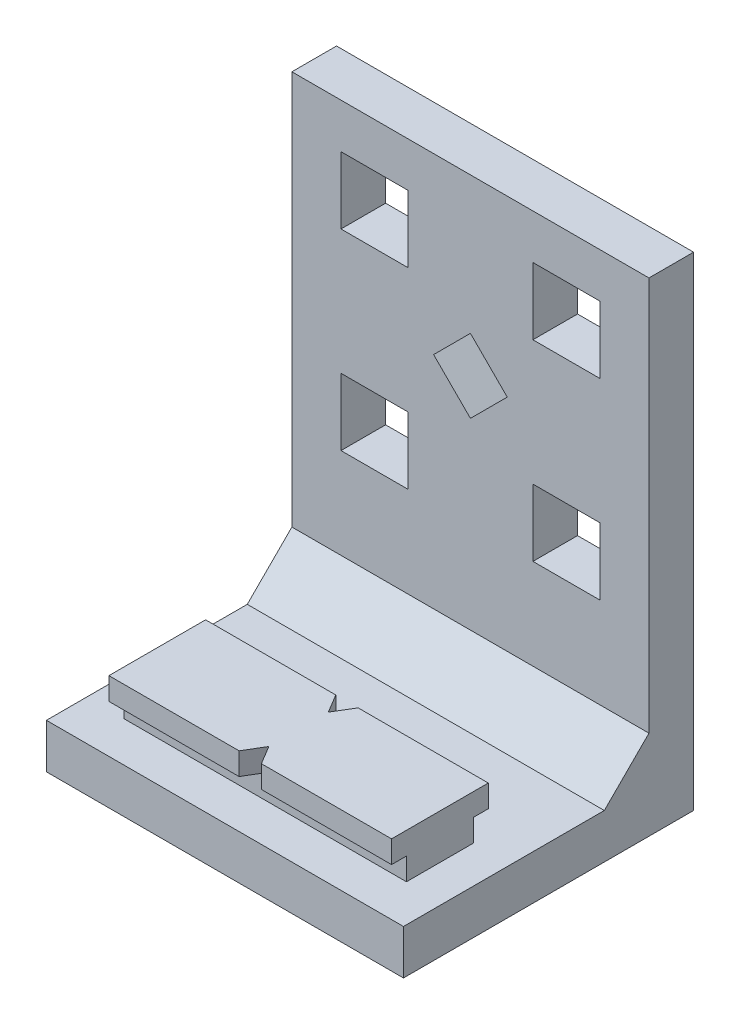
SolidWorks part; units mm, degrees
ref_plane "Front Plane" through (0, 0, 0) normal (0, 0, 1) x (1, 0, 0)
ref_plane "Top Plane" through (0, 0, 0) normal (0, 1, 0) x (1, 0, 0)
ref_plane "Right Plane" through (0, 0, 0) normal (1, 0, 0) x (0, 0, -1)
sketch "Sketch1" plane through (0, 0, 0) normal (0, 1, 0) x (1, 0, 0)
  line L1 (-12, -9.75) -> (12, -9.75)
  line L2 (-12, -9.75) -> (-12, 9.75)
  line L3 (-12, 9.75) -> (12, 9.75)
  line L4 (12, -9.75) -> (12, 9.75)
  line L5 (-12, -9.75) -> (12, 9.75) construction
  line L6 (-12, 9.75) -> (12, -9.75) construction
  point P0 (0, 0)
  dimension "D1" = 19.5
  dimension "D2" = 24
extrude "Boss-Extrude1" add sketch "Sketch1" along normal blind 3
sketch "Sketch3" plane through (0, 3, 0) normal (0, 1, 0) x (1, 0, 0)
  line L0 (-12, -9.75) -> (12, -9.75) construction
  line L1 (-9.5, -7.05) -> (9.5, -7.05)
  line L2 (-9.5, -7.05) -> (-9.5, -2.55)
  line L3 (-9.5, -2.55) -> (9.5, -2.55)
  line L4 (9.5, -7.05) -> (9.5, -2.55)
  line L5 (-9.5, -7.05) -> (9.5, -2.55) construction
  line L6 (-9.5, -2.55) -> (9.5, -7.05) construction
  point P0 (0, -4.8)
  dimension "D1" = 4.5
  dimension "D2" = 2.7
  dimension "D3" = 19
extrude "Boss-Extrude2" add sketch "Sketch3" along normal blind 1.5
sketch "Sketch4" plane through (0, 4.5, 0) normal (0, 1, 0) x (1, 0, 0)
  line L3 (9.5, -7.05) -> (9.5, -2.55) construction
  line L4 (-9.5, -8.05) -> (9.5, -8.05)
  line L5 (-9.5, -8.05) -> (-9.5, -1.55)
  line L6 (-9.5, -1.55) -> (9.5, -1.55)
  line L7 (9.5, -8.05) -> (9.5, -1.55)
  line L8 (-9.5, -8.05) -> (9.5, -1.55) construction
  line L9 (-9.5, -1.55) -> (9.5, -8.05) construction
  line L10 (-9.5, -2.55) -> (-9.5, -7.05) construction
  line L11 (9.5, -2.55) -> (-9.5, -2.55) construction
  line L12 (-9.5, -7.05) -> (9.5, -7.05) construction
  point P4 (0, -4.8)
  dimension "D1" = 1
  dimension "D2" = 1
extrude "Boss-Extrude3" add sketch "Sketch4" along normal blind 1.5
sketch "Sketch5" plane through (0, 6, 0) normal (0, 1, 0) x (1, 0, 0)
  line L0 (0, -2.8) -> (0.75, -1.55)
  line L1 (9.5, -1.55) -> (-9.5, -1.55) construction
  line L2 (0.75, -1.55) -> (-0.75, -1.55)
  line L3 (-0.75, -1.55) -> (0, -2.8)
  line L4 (0, -6.8) -> (0.75, -8.05)
  line L5 (-9.5, -8.05) -> (9.5, -8.05) construction
  line L6 (0.75, -8.05) -> (-0.75, -8.05)
  line L7 (-0.75, -8.05) -> (0, -6.8)
  dimension "D1" = 1.25
  dimension "D2" = 1.25
  dimension "D3" = 1.5
  dimension "D4" = 1.5
  dimension "D5" = 0.75
  dimension "D6" = 0.75
extrude "Cut-Extrude1" cut sketch "Sketch5" against normal up to surface (1.5 mm away) up to face at (-2.375, 4.5, 7.55)
sketch "Sketch6" plane through (0, 3, 0) normal (0, 1, 0) x (1, 0, 0)
  line L0 (12, -9.75) -> (12, 9.75) construction
  line L1 (-12, 9.75) -> (12, 9.75)
  line L2 (-12, 9.75) -> (-12, 6.75)
  line L3 (-12, 6.75) -> (12, 6.75)
  line L4 (12, 9.75) -> (12, 6.75)
  dimension "D1" = 3
extrude "Boss-Extrude4" add sketch "Sketch6" along normal blind 29.5
sketch "Sketch7" plane through (0, 0, -6.75) normal (0, 0, 1) x (1, 0, 0)
  line L0 (0, 29.1503) -> (0, 10.2027) construction
  line L1 (-8.7, 25) -> (-4.2, 25)
  line L2 (-8.7, 25) -> (-8.7, 29.5)
  line L3 (-8.7, 29.5) -> (-4.2, 29.5)
  line L4 (-4.2, 25) -> (-4.2, 29.5)
  line L5 (-8.7, 25) -> (-4.2, 29.5) construction
  line L6 (-8.7, 29.5) -> (-4.2, 25) construction
  line L7 (-8.7, 12.1) -> (-4.2, 12.1)
  line L8 (-8.7, 12.1) -> (-8.7, 16.6)
  line L9 (-8.7, 16.6) -> (-4.2, 16.6)
  line L10 (-4.2, 12.1) -> (-4.2, 16.6)
  line L11 (-8.7, 12.1) -> (-4.2, 16.6) construction
  line L12 (-8.7, 16.6) -> (-4.2, 12.1) construction
  line L13 (-12, 32.5) -> (12, 32.5) construction
  line L14 (8.7, 16.6) -> (4.2, 12.1) construction
  line L15 (8.7, 12.1) -> (4.2, 16.6) construction
  line L16 (8.7, 29.5) -> (4.2, 25) construction
  line L17 (8.7, 25) -> (4.2, 29.5) construction
  line L18 (4.2, 12.1) -> (4.2, 16.6)
  line L19 (8.7, 16.6) -> (4.2, 16.6)
  line L20 (8.7, 12.1) -> (8.7, 16.6)
  line L21 (8.7, 12.1) -> (4.2, 12.1)
  line L22 (4.2, 25) -> (4.2, 29.5)
  line L23 (8.7, 29.5) -> (4.2, 29.5)
  line L24 (8.7, 25) -> (8.7, 29.5)
  line L25 (8.7, 25) -> (4.2, 25)
  line L26 (-2.4749, 20.8) -> (0, 23.2749)
  line L27 (0, 23.2749) -> (2.4749, 20.8)
  line L28 (2.4749, 20.8) -> (0, 18.3251)
  line L29 (0, 18.3251) -> (-2.4749, 20.8)
  point P0 (-6.45, 27.25)
  point P5 (-6.45, 14.35)
  point P23 (6.45, 14.35)
  point P24 (6.45, 27.25)
  dimension "D1" = 4.5
  dimension "D2" = 17.4
  dimension "D3" = 8.7
  dimension "D4" = 3
  dimension "D5" = 3.5
  dimension "D6" = 8.7
extrude "Cut-Extrude2" cut sketch "Sketch7" against normal through all
chamfer "Chamfer1" distance 3 angle 45 1 edges at (0, 3, -6.75)
